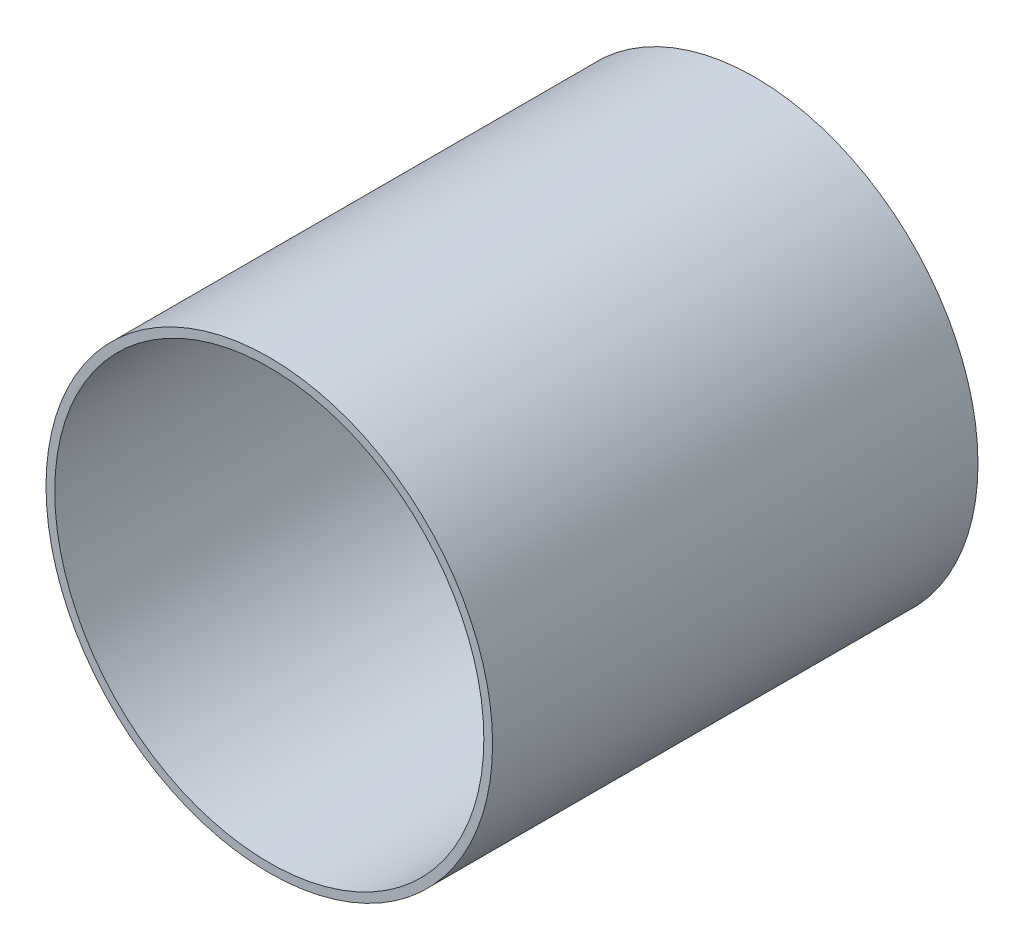
SolidWorks part; units mm, degrees
ref_plane "Front Plane" through (0, 0, 0) normal (0, 0, 1) x (1, 0, 0)
ref_plane "Top Plane" through (0, 0, 0) normal (0, 1, 0) x (1, 0, 0)
ref_plane "Right Plane" through (0, 0, 0) normal (1, 0, 0) x (0, 0, -1)
sketch "Sketch1" plane through (0, 0, 0) normal (0, 0, 1) x (1, 0, 0)
  circle A0 centre (0, 0) radius 11.05
  circle A1 centre (0, 0) radius 11.5
  dimension "D1" = 23
  dimension "D2" = 22.1
extrude "Boss-Extrude1" add sketch "Sketch1" along normal blind 25
